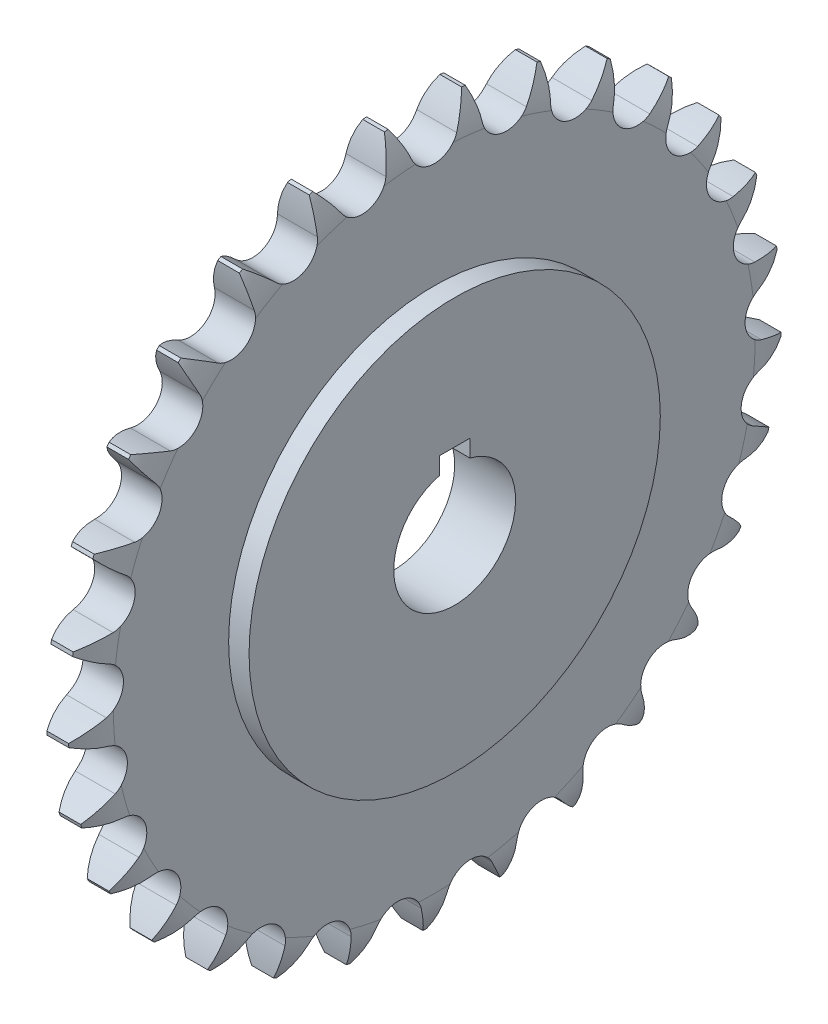
SolidWorks part; units mm, degrees
ref_plane "Plane1" through (0, 0, 0) normal (0, 0, 1) x (1, 0, 0)
ref_plane "Plane2" through (0, 0, 0) normal (0, 1, 0) x (1, 0, 0)
ref_plane "Plane3" through (0, 0, 0) normal (1, 0, 0) x (0, 0, -1)
sketch "Clipboard" plane through (0, 0, 0) normal (0, 1, 0) x (1, 0, 0)
  line L0 (0, 0) -> (8.3308, -4.6178)
  line L1 (-15, 0) -> (100, 0) construction
  line L2 (0, 0) -> (-0.8203, 0.9272)
  line L3 (0, 0) -> (-8.8973, 3.4006)
  line L4 (0, 0) -> (2.7113, 1.5029)
  line L5 (0, 0) -> (-46.8476, -17.4728)
  line L6 (0, 0) -> (-4.4098, -2.9753)
  line L7 (-0.8203, 0.9272) -> (42.4814, 25.9274)
  line L8 (-76.2, 38.1) -> (-73.4, 38.1)
  line L9 (-73.3242, 40.7328) -> (-72.926, 40.7699)
  line L10 (-73.4529, 9.1872) -> (-63.2129, 9.1872)
  circle A0 centre (0, 0) radius 3.175
  circle A1 centre (0, 0) radius 37.5
  circle A2 centre (0, 0) radius 37.5
  dimension "Dr" = 6.35
  dimension "MHD" = 75
  dimension "Hub_dia" = 75
  dimension "Num_teeth" = 29
  dimension "Pitch" = 9.525
  dimension "Width" = 3.1
  dimension "Side_relief" = 1.238
  dimension "Side_radius" = 9.525
  dimension "Overall_len" = 50
  dimension "Show_teeth" = 29
  dimension "Thickness" = 5.3196
  dimension "OAL" = 50.0005
  dimension "T_dim" = 2.8
  dimension "Fillet_rad" = 0.4
  dimension "Face_width" = 5.32
  dimension "Num_strands" = 1
  dimension "Transv_pitch" = 10.24
  dimension "Plate_wid" = 8.26
sketch "BasProSke" plane through (0, 0, 0) normal (0, 1, 0) x (1, 0, 0)
  line L0 (-10, 0) -> (60, 0) construction
  line L1 (0, 0) -> (0, 42.1309)
  line L2 (0, 0) -> (5.3196, 0)
  line L3 (5.3196, 0) -> (5.3196, 42.1309)
  line L4 (4.0816, 46.8268) -> (1.238, 46.8268)
  arc A0 (0, 42.1309) -> (1.238, 46.8268) centre (9.525, 42.1309) cw
  arc A1 (5.3196, 42.1309) -> (4.0816, 46.8268) centre (-4.2054, 42.1309) ccw
  dimension "Thickness" = 5.3196
  dimension "D1" = 9.525
  dimension "G1" = 1.238
  dimension "G2" = 1.238
  dimension "Diameter" = 93.6536
revolve "Base-Revolve" add sketch "BasProSke" angle 360 about L0
sketch "TooCutSke" plane through (0, 0, 0) normal (1, 0, 0) x (0, 0, -1)
  line L0 (0, 44.0804) -> (2.9826, 42.9025) construction
  line L1 (0, 0) -> (0, 107) construction
  line L2 (0, 44.0804) -> (-10, 44.0804) construction
  line L3 (0, 44.0804) -> (-2.9826, 42.9025) construction
  arc A0 (2.9826, 42.9025) -> (5.1154, 47.0495) centre (24.9531, 34.2251) cw
  arc A1 (2.9826, 42.9025) -> (-2.9826, 42.9025) centre (0, 44.0804) cw
  arc A2 (-2.9826, 42.9025) -> (-5.1154, 47.0495) centre (-24.9531, 34.2251) ccw
  arc A3 (5.1154, 47.0495) -> (-5.1154, 47.0495) centre (0, 0) ccw
  dimension "R1" = 3.2067
  dimension "R2" = 23.622
  dimension "Overcut" = 47.3268
  dimension "Seat_radius" = 44.0804
  dimension "X" = 136.897
extrude "ToothCut" cut sketch "TooCutSke" along normal through all
pattern_circular "TeethCuts" count 29 every 12.414 about axis through (-10, 0, 0) along (1, 0, 0) of "ToothCut"
sketch "HubNeaOneSke" plane through (0, 0, 0) normal (-1, 0, 0) x (0, 0, 1)
  circle A0 centre (0, 0) radius 37.5
  dimension "Diameter" = 75
extrude "HubNearOne" [suppressed] add sketch "HubNeaOneSke" along normal blind 44.6809
fillet "HubNearOneFillet" [suppressed] radius 0.4
sketch "HubNeaBotSke" plane through (0, 0, 0) normal (-1, 0, 0) x (0, 0, 1)
  circle A0 centre (0, 0) radius 37.5
  dimension "Diameter" = 75
extrude "HubNearBoth" [suppressed] add sketch "HubNeaBotSke" along normal blind 22.3405
fillet "HubNearBothFillet" [suppressed] radius 0.4
ref_plane "FarPln" through (5.3196, 0, 0) normal (1, 0, 0) x (0, 0, -1)
sketch "HubFarSke" plane through (5.3196, 0, 0) normal (1, 0, 0) x (0, 0, -1)
  circle A0 centre (0, 0) radius 37.5
  dimension "Diameter" = 75
extrude "HubFar" [suppressed] add sketch "HubFarSke" along normal blind 22.3405
fillet "HubFarFillet" [suppressed] radius 0.4
sketch "BorSke" plane through (0, 0, 0) normal (1, 0, 0) x (0, 0, -1)
  circle A0 centre (0, 0) radius 10
  dimension "Diameter" = 20
extrude "Bore" cut sketch "BorSke" along normal mid plane 100.001
sketch "KeySke" plane through (0, 0, 0) normal (1, 0, 0) x (0, 0, -1)
  line L0 (-3, 0) -> (-3, 12.8)
  line L1 (-3, 12.8) -> (3, 12.8)
  line L2 (3, 12.8) -> (3, 0)
  line L3 (0, 0) -> (0, 34) construction
  line L4 (-3, 0) -> (3, 0)
  dimension "Offset" = 12.8
  dimension "Width" = 6
extrude "Keyway" [suppressed] cut sketch "KeySke" along normal mid plane 100.001
pattern_circular "Keyway2" [suppressed] count 2 every 90 about axis through (-10, 0, 0) along (1, 0, 0)
sketch "Sketch1" plane through (5.3196, 0, 0) normal (1, 0, 0) x (0, 0, -1)
  circle A0 centre (0, 0) radius 27
  circle A1 centre (0, 0) radius 6
  dimension "D1" = 54
  dimension "D2" = 12
extrude "Boss-Extrude1" add sketch "Sketch1" along normal offset from surface (22.6804 mm away) 28 up to face at (0, 0, -10)
sketch "Sketch2" plane through (28, 0, 0) normal (1, 0, 0) x (0, 0, -1)
  circle A0 centre (0, 0) radius 39.4959
extrude "trim boss" cut sketch "Sketch2" against normal blind 20
sketch "Sketch3" plane through (8, 0, 0) normal (1, 0, 0) x (0, 0, -1)
  circle A0 centre (0, 0) radius 8
  dimension "D1" = 16
extrude "bore centre" cut sketch "Sketch3" against normal blind 20
sketch "Sketch5" plane through (5.3196, 0, 0) normal (-1, 0, 0) x (0, 0, 1)
  circle A0 centre (0, 0) radius 8 construction
  circle A1 centre (0, 0) radius 10 construction
  circle A2 centre (0, 0) radius 8
  circle A3 centre (0, 0) radius 10
extrude "Boss-Extrude2" add sketch "Sketch5" along normal up to surface (5.3196 mm away) up to face at (0, 0, -10)
sketch "Sketch4" plane through (0, 0, 0) normal (-1, 0, 0) x (0, 0, 1)
  line L0 (-2, 10) -> (-2, 6)
  line L1 (-2, 10) -> (2, 10)
  line L2 (-2, 6) -> (2, 6)
  line L3 (2, 10) -> (2, 6)
  line L4 (-2, 10) -> (2, 6) construction
  line L5 (-2, 6) -> (2, 10) construction
  line L6 (0, 0) -> (0, 8) construction
  circle A0 centre (0, 0) radius 8 construction
  point P1 (0, 8)
  dimension "D1" = 4
  dimension "D2" = 4
extrude "Cut-Extrude1" cut sketch "Sketch4" against normal blind 10
equation "' \"Pitch@Clipboard\" = 12.7"
equation "' \"Num_strands@Clipboard\" = 1"
equation "' \"Num_teeth@Clipboard\" = 9"
equation "' \"Hub_dia@Clipboard\" = 50"
equation "' \"Overall_len@Clipboard\" = 3"
equation "' \"Diameter@BorSke\" = 12"
equation "' \"T_dim@Clipboard\" = 1"
equation "' \"Width@KeySke\" = 2"
equation "' \"Dr@Clipboard\" = 8.51"
equation "' \"Face_width@Clipboard\" = 7.2"
equation "' \"Side_radius@Clipboard\" = 12.7"
equation "' \"Side_relief@Clipboard\" = 1.27"
equation "' \"Transv_pitch@Clipboard\" = 13.92"
equation "' \"Show_teeth@Clipboard\" = 9"
equation "' \"Fillet_rad@Clipboard\" = 0.6"
equation "' \"Plate_wid@Clipboard\" = 11.8"
equation "\"Num_teeth@Clipboard\" = int( \"Num_teeth@Clipboard\" )"
equation "\"Num_teeth@Clipboard\" = ((sgn( \"Num_teeth@Clipboard\" - 5.0)+1)*( \"Num_teeth@Clipboard\" - 5.0))/2 +5.0"
equation "\"Num_teeth@Clipboard\" = ((sgn( \"Num_teeth@Clipboard\" - 200.0)-1)*( \"Num_teeth@Clipboard\" - 200.0))/-2 +200.0"
equation "\"MHD@Clipboard\" = \"Pitch@Clipboard\" * (1.0 / tan(3.14159265 / \"Num_teeth@Clipboard\" )) - 1.04 * \"Plate_wid@Clipboard\" - 0.76"
equation "\"Thickness@Clipboard\"  = \"Face_width@Clipboard\" + (\"Num_strands@Clipboard\" - 1) * \"Transv_pitch@Clipboard\""
equation "\"OAL@Clipboard\" = \"Thickness@Clipboard\" + 2 * \"Fillet_rad@Clipboard\" + 1"
equation "\"MHD@Clipboard\" = ((sgn( \"MHD@Clipboard\" - \"Hub_dia@Clipboard\" )-1)*( \"MHD@Clipboard\" - \"Hub_dia@Clipboard\" ))/-2+ \"Hub_dia@Clipboard\""
equation "\"OAL@Clipboard\" = ((sgn( \"OAL@Clipboard\" - \"Overall_len@Clipboard\" )+1)*( \"OAL@Clipboard\" - \"Overall_len@Clipboard\" ))/2 + \"Overall_len@Clipboard\" + 0.0005"
equation "\"Num_teeth@TeethCuts\" = int( \"Show_teeth@Clipboard\" ) + 1"
equation "\"Num_teeth@TeethCuts\" = ((sgn( \"Num_teeth@TeethCuts\" - \"Num_teeth@Clipboard\" )-1)*( \"Num_teeth@TeethCuts\" - \"Num_teeth@Clipboard\" ))/-2+ \"Num_teeth@Clipboard\""
equation "\"Num_teeth@TeethCuts\" = ((sgn( \"Num_teeth@TeethCuts\" - 2.0)+1)*( \"Num_teeth@TeethCuts\" - 2.0))/2 +2.0"
equation "\"Angle@TeethCuts\" = 360.0 / \"Num_teeth@Clipboard\""
equation "\"Seat_radius@TooCutSke\" = ( \"Pitch@Clipboard\" / 2.0) / sin(3.14159265 / \"Num_teeth@Clipboard\" ) - \"Dr@Clipboard\" / 2.0 + \"Dr@Clipboard\" * 0.505"
equation "\"R1@TooCutSke\"  = \"Dr@Clipboard\" * 0.505"
equation "\"X@TooCutSke\" = 140.0 - (90.0 / \"Num_teeth@Clipboard\")"
equation "\"R2@TooCutSke\" = 0.12 * \"Dr@Clipboard\" * ( \"Num_teeth@Clipboard\" + 2.0)"
equation "\"Overcut@TooCutSke\" = 0.5 + 0.625 * \"Pitch@Clipboard\" - 0.5 * \"Dr@Clipboard\"  +  \"Pitch@Clipboard\" / 2.0 / sin(3.14159265 / \"Num_teeth@Clipboard\" )"
equation "\"Diameter@BasProSke\" = 2.0 * ( 0.625 * \"Pitch@Clipboard\" - 0.5 * \"Dr@Clipboard\"  +  \"Pitch@Clipboard\" / 2.0 / sin(3.14159265 / \"Num_teeth@Clipboard\" ))"
equation "\"Thickness@BasProSke\"  = \"Thickness@Clipboard\""
equation "\"G1@BasProSke\" =  \"Side_relief@Clipboard\""
equation "\"G2@BasProSke\" =  \"Side_relief@Clipboard\""
equation "\"D1@BasProSke\" =  \"Side_radius@Clipboard\""
equation "\"Diameter@HubNeaOneSke\" = \"MHD@Clipboard\""
equation "\"Length@HubNearOne\" = \"OAL@Clipboard\" - \"Thickness@BasProSke\""
equation "\"Diameter@HubNeaBotSke\" = \"MHD@Clipboard\""
equation "\"Length@HubNearBoth\" = ( \"OAL@Clipboard\" - \"Thickness@BasProSke\" ) / 2.0"
equation "\"D1@HubNearOneFillet\" = \"Fillet_rad@Clipboard\""
equation "\"D1@HubNearBothFillet\" = \"Fillet_rad@Clipboard\""
equation "\"Thickness@FarPln\" = \"Thickness@BasProSke\""
equation "\"Diameter@HubFarSke\" = \"MHD@Clipboard\""
equation "\"Length@HubFar\" = ( \"OAL@Clipboard\" - \"Thickness@BasProSke\" ) / 2.0"
equation "\"D1@HubFarFillet\" = \"Fillet_rad@Clipboard\""
equation "\"D1@Bore\" = \"OAL@Clipboard\" * 2.0"
equation "\"D1@Keyway\" = \"OAL@Clipboard\" * 2.0"
equation "\"Offset@KeySke\" = \"T_dim@Clipboard\" + \"Diameter@BorSke\" / 2.0"
